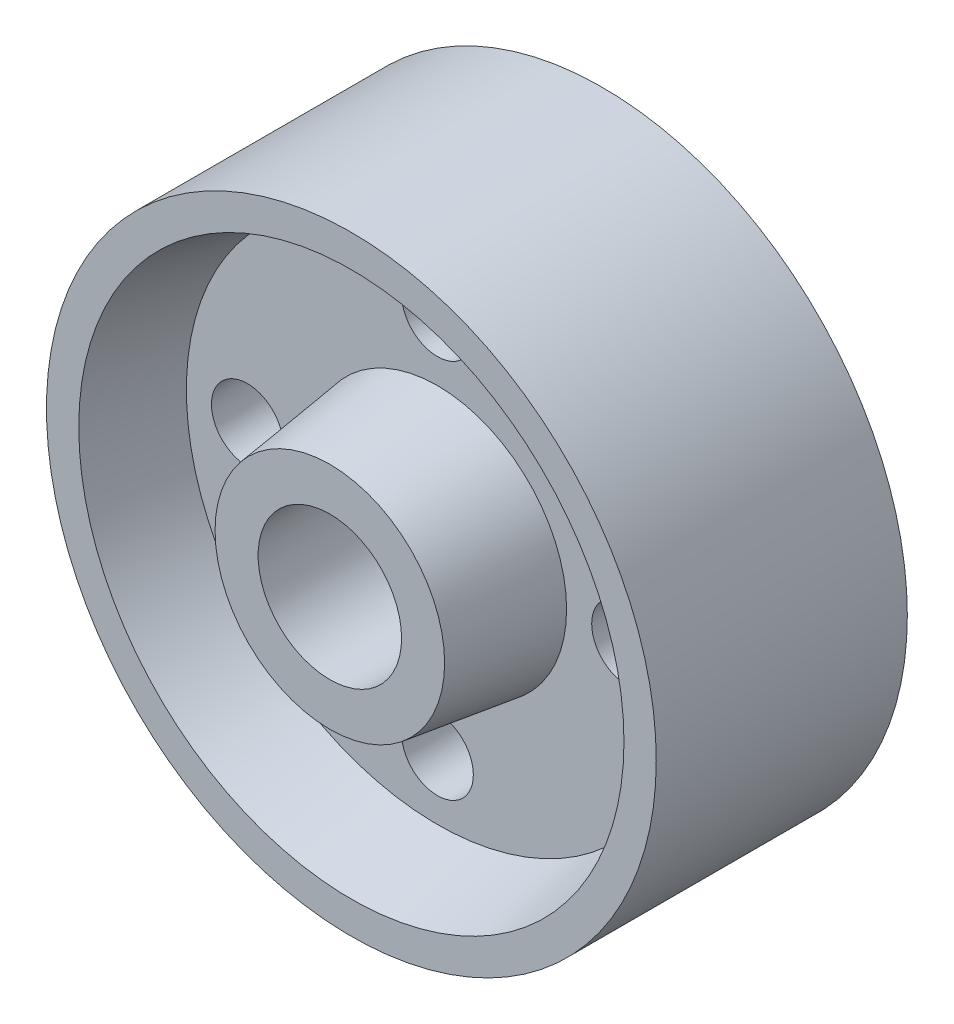
SolidWorks part; units mm, degrees
ref_plane "Front Plane" through (0, 0, 0) normal (0, 0, 1) x (1, 0, 0)
ref_plane "Top Plane" through (0, 0, 0) normal (0, 1, 0) x (1, 0, 0)
ref_plane "Right Plane" through (0, 0, 0) normal (1, 0, 0) x (0, 0, -1)
sketch "Sketch2" plane through (0, 0, 0) normal (1, 0, 0) x (0, 0, -1)
  line L0 (-152.0187, 0) -> (152.0187, 0) construction
  line L1 (0, 114.8698) -> (0, -114.8698) construction
  line L2 (-17.5, 42.5) -> (17.5, 42.5)
  line L3 (17.5, 42.5) -> (17.5, 38)
  line L4 (17.5, 38) -> (5.5, 35)
  line L5 (5.5, 35) -> (5.5, 18)
  line L6 (5.5, 18) -> (20.5, 16)
  line L7 (20.5, 16) -> (20.5, 0)
  line L8 (-20.5, 16) -> (-20.5, 0)
  line L9 (-5.5, 18) -> (-20.5, 16)
  line L10 (-5.5, 35) -> (-5.5, 18)
  line L11 (-17.5, 38) -> (-5.5, 35)
  line L12 (-17.5, 42.5) -> (-17.5, 38)
  line L13 (20.5, 0) -> (-20.5, 0)
  point P3 (0, 0)
  point P4 (0, 0)
  point P8 (0, 0)
  point P21 (0, 42.5)
  dimension "D1" = 42.5
  dimension "D2" = 38
  dimension "D3" = 35
  dimension "D4" = 18
  dimension "D5" = 16
  dimension "D6" = 17.5
  dimension "D7" = 5.5
  dimension "D8" = 20.5
revolve "Revolve1" add sketch "Sketch2" angle 360 about L0
sketch "Sketch3" plane through (0, 0, 20.5) normal (0, 0, 1) x (1, 0, 0)
  line L0 (-78.1399, 0) -> (78.1399, 0) construction
  line L1 (0, -65.8658) -> (0, 65.8658) construction
  circle A0 centre (0, 0) radius 10
  circle A1 centre (0, 0) radius 26.5 construction
  circle A2 centre (0, 26.5) radius 5
  circle A3 centre (26.5, 0) radius 5
  circle A4 centre (0, -26.5) radius 5
  circle A5 centre (-26.5, 0) radius 5
  point P5 (0, 0)
  point P9 (0, 0)
  point P14 (-25.8424, -5.8667)
  point P23 (0, 0)
  dimension "D1" = 20
  dimension "D2" = 53
  dimension "D3" = 10
  dimension "D4" = 4
extrude "Cut-Extrude1" cut sketch "Sketch3" against normal through all
